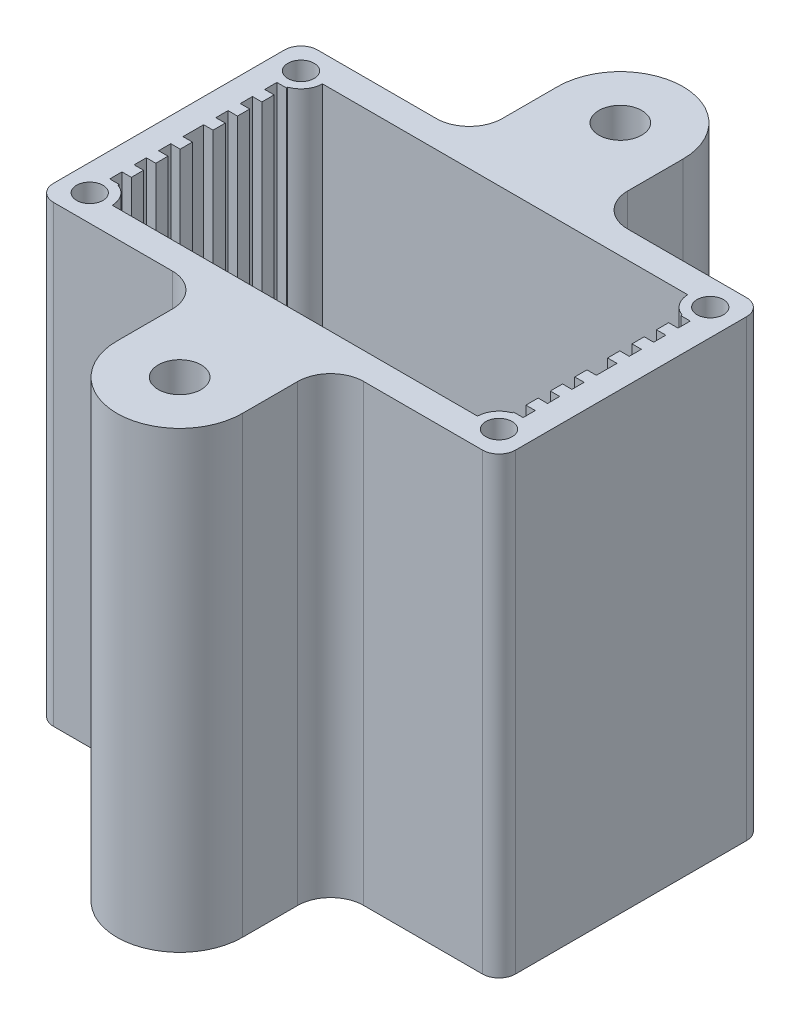
SolidWorks part; units mm, degrees
ref_plane "Front Plane" through (0, 0, 0) normal (0, 0, 1) x (1, 0, 0)
ref_plane "Top Plane" through (0, 0, 0) normal (0, 1, 0) x (1, 0, 0)
ref_plane "Right Plane" through (0, 0, 0) normal (1, 0, 0) x (0, 0, -1)
sketch "Sketch1" plane through (0, 0, 0) normal (0, 1, 0) x (1, 0, 0)
  line L0 (-48.5484, 0) -> (60.708, 0) construction
  line L1 (-31.8135, 16.1811) -> (31.8135, 16.1811) construction
  line L2 (-31.8135, 16.1811) -> (-31.8135, -16.1811) construction
  line L3 (-31.8135, -16.1811) -> (31.8135, -16.1811) construction
  line L4 (31.8135, 16.1811) -> (31.8135, -16.1811) construction
  line L5 (-31.8135, 16.1811) -> (31.8135, -16.1811) construction
  line L6 (-31.8135, -16.1811) -> (31.8135, 16.1811) construction
  line L11 (-30.3657, -16.1811) -> (30.3657, -16.1811) construction
  line L12 (-30.3657, -16.1811) -> (-30.3657, 16.1811) construction
  line L13 (-30.3657, 16.1811) -> (30.3657, 16.1811) construction
  line L14 (30.3657, -16.1811) -> (30.3657, 16.1811) construction
  line L15 (-30.3657, -16.1811) -> (30.3657, 16.1811) construction
  line L16 (-30.3657, 16.1811) -> (30.3657, -16.1811) construction
  line L17 (-31.8135, 10.9868) -> (31.8135, 10.9868) construction
  line L18 (-31.8135, 16.1811) -> (31.8135, 16.1811) construction
  line L19 (-31.8135, 16.1811) -> (-31.8135, 12.8664) construction
  line L20 (-31.8135, 12.8664) -> (31.8135, 12.8664) construction
  line L21 (31.8135, 16.1811) -> (31.8135, 12.8664) construction
  line L22 (-31.8135, 9.1072) -> (31.8135, 9.1072) construction
  line L23 (-31.8135, 7.2276) -> (31.8135, 7.2276) construction
  line L24 (-31.8135, 5.348) -> (31.8135, 5.348) construction
  line L25 (-31.8135, 3.4684) -> (31.8135, 3.4684) construction
  line L26 (-31.8135, 1.5888) -> (31.8135, 1.5888) construction
  line L27 (30.3657, 16.1811) -> (-30.3657, 16.1811)
  line L29 (-35.56, 0) -> (-35.56, 20.32)
  line L30 (-35.56, 20.32) -> (35.56, 20.32)
  line L31 (35.56, 0) -> (35.56, 20.32)
  line L32 (-33.4219, -19.0982) -> (35.56, 20.32) construction
  line L33 (-35.56, 20.32) -> (33.4219, -19.0982) construction
  line L34 (-30.3657, 16.1811) -> (-30.3657, 12.8664)
  line L35 (-30.3657, 12.8664) -> (-31.8135, 12.8664)
  line L36 (-31.8135, 12.8664) -> (-31.8135, 10.9868)
  line L37 (-31.8135, 10.9868) -> (-30.3657, 10.9868)
  line L38 (-30.3657, 10.9868) -> (-30.3657, 9.1072)
  line L39 (-30.3657, 9.1072) -> (-31.8135, 9.1072)
  line L40 (-31.8135, 9.1072) -> (-31.8135, 7.2276)
  line L41 (-31.8135, 7.2276) -> (-30.3657, 7.2276)
  line L42 (-30.3657, 7.2276) -> (-30.3657, 5.348)
  line L43 (-30.3657, 5.348) -> (-31.8135, 5.348)
  line L44 (-31.8135, 5.348) -> (-31.8135, 3.4684)
  line L45 (-31.8135, 3.4684) -> (-30.3657, 3.4684)
  line L46 (-30.3657, 3.4684) -> (-30.3657, 1.5888)
  line L47 (-30.3657, 1.5888) -> (-31.8135, 1.5888)
  line L48 (-31.8135, 1.5888) -> (-31.8135, 0)
  line L49 (-31.8135, 0) -> (-35.56, 0)
  line L50 (30.3657, 16.1811) -> (30.3657, 12.8664)
  line L51 (30.3657, 12.8664) -> (31.8135, 12.8664)
  line L52 (31.8135, 12.8664) -> (31.8135, 10.9868)
  line L53 (31.8135, 10.9868) -> (30.3657, 10.9868)
  line L54 (30.3657, 10.9868) -> (30.3657, 9.1072)
  line L55 (30.3657, 9.1072) -> (31.8135, 9.1072)
  line L56 (31.8135, 9.1072) -> (31.8135, 7.2276)
  line L57 (31.8135, 7.2276) -> (30.3657, 7.2276)
  line L58 (30.3657, 7.2276) -> (30.3657, 5.348)
  line L59 (30.3657, 5.348) -> (31.8135, 5.348)
  line L60 (31.8135, 5.348) -> (31.8135, 3.4684)
  line L61 (31.8135, 3.4684) -> (30.3657, 3.4684)
  line L62 (30.3657, 3.4684) -> (30.3657, 1.5888)
  line L63 (30.3657, 1.5888) -> (31.8135, 1.5888)
  line L64 (31.8135, 1.5888) -> (31.8135, 0)
  line L65 (31.8135, 0) -> (35.56, 0)
  point P0 (0, 0)
  point P6 (0, 0)
  point P27 (0, 0)
  dimension "D1" = 32.3621
  dimension "D2" = 63.627
  dimension "D3" = 60.7314
  dimension "D4" = 3.3147
  dimension "D5" = 1.8796
  dimension "D6" = 1.8796
  dimension "D7" = 1.8796
  dimension "D8" = 1.8796
  dimension "D9" = 1.8796
  dimension "D10" = 1.8796
  dimension "D12" = 20.32
  dimension "D11" = 35.56
  dimension "D13" = 35.56
extrude "Boss-Extrude1" add sketch "Sketch1" along normal blind 69.85
sketch "Sketch2" plane through (0, 0, 0) normal (0, 0, 1) x (1, 0, 0)
  line L0 (-31.8135, 69.85) -> (-35.56, 0) construction
  line L1 (-31.8135, 0) -> (-35.56, 69.85) construction
  line L2 (-35.56, 69.85) -> (-31.8135, 69.85) construction
  line L3 (-32.7469, 0) -> (-34.6265, 0)
  line L4 (-32.7469, 0) -> (-32.7469, 69.85)
  line L5 (-32.7469, 69.85) -> (-34.6265, 69.85)
  line L6 (-34.6265, 0) -> (-34.6265, 69.85)
  line L7 (-32.7469, 0) -> (-34.6265, 69.85) construction
  line L8 (-32.7469, 69.85) -> (-34.6265, 0) construction
  point P8 (-33.6867, 34.925)
  dimension "D1" = 1.8796
sketch "Sketch3" plane through (0, 0, 0) normal (0, 0, 1) x (1, 0, 0)
  line L0 (35.56, 69.85) -> (31.8135, 0) construction
  line L1 (35.56, 0) -> (31.8135, 69.85) construction
  line L2 (31.8135, 69.85) -> (35.56, 69.85) construction
  line L3 (32.7342, 0) -> (34.6392, 0)
  line L4 (32.7342, 0) -> (32.7342, 69.85)
  line L5 (32.7342, 69.85) -> (34.6392, 69.85)
  line L6 (34.6392, 0) -> (34.6392, 69.85)
  line L7 (32.7342, 0) -> (34.6392, 69.85) construction
  line L8 (32.7342, 69.85) -> (34.6392, 0) construction
  point P8 (33.6867, 34.925)
  dimension "D1" = 1.905
fillet "Fillet1" radius 2.54 2 edges at (-35.56, 34.925, -20.32) (35.56, 34.925, -20.32)
sketch "Sketch4" plane through (0, 0, 0) normal (0, 1, 0) x (1, 0, 0)
  line L0 (-35.56, 0) -> (35.56, 0) construction
  line L1 (0, 0) -> (0, 20.32) construction
  line L2 (33.02, 20.32) -> (-33.02, 20.32) construction
  line L4 (-9.652, 33.909) -> (-9.652, 20.32)
  line L5 (-9.652, 20.32) -> (9.652, 20.32)
  line L6 (9.652, 33.909) -> (9.652, 20.32)
  line L7 (0, 24.257) -> (0, 33.909) construction
  circle A0 centre (0, 33.909) radius 3.302
  arc A1 (9.652, 33.909) -> (-9.652, 33.909) centre (0, 33.909) ccw
  dimension "D2" = 6.604
  dimension "D3" = 19.304
  dimension "D1" = 33.909
extrude "Boss-Extrude3" add sketch "Sketch4" along normal through all
fillet "Fillet2" radius 5.08 2 edges at (-9.652, 34.925, -20.32) (9.652, 34.925, -20.32)
sketch "Sketch5" plane through (0, 69.85, 0) normal (0, 1, 0) x (1, 0, 0)
  line L0 (-31.496, 20.32) -> (-31.496, 16.256) construction
  line L1 (-14.732, 20.32) -> (-33.02, 20.32) construction
  line L2 (-31.496, 16.256) -> (-35.56, 16.256) construction
  line L3 (-35.56, 17.78) -> (-35.56, 0) construction
  circle A0 centre (-31.496, 16.256) radius 3.3896
extrude "Boss-Extrude4" add sketch "Sketch5" against normal up to surface (69.85 mm away) up to face at (0, 0, -10.8816)
mirror "Mirror1" about plane through (0, 0, 0) normal (0, 0, 1) of "Boss-Extrude1", "Fillet1", "Boss-Extrude3", "Fillet2"
mirror "Mirror2" about plane through (0, 0, 0) normal (0, 0, 1) of "Boss-Extrude4" second plane through (0, 0, 0) second plane normal (1, 0, 0)
sketch "Sketch6" plane through (0, 69.85, 0) normal (0, 1, 0) x (1, 0, 0)
  line L0 (-31.496, 20.32) -> (-31.496, 16.256) construction
  line L1 (-14.732, 20.32) -> (-33.02, 20.32) construction
  line L2 (-31.496, 16.256) -> (-35.56, 16.256) construction
  line L3 (-35.56, 17.78) -> (-35.56, -17.78) construction
  circle A0 centre (-31.496, 16.256) radius 2.032
extrude "Cut-Extrude1" cut sketch "Sketch6" against normal through all
mirror "Mirror3" about plane through (0, 0, 0) normal (0, 0, 1) of "Cut-Extrude1" second plane through (0, 0, 0) second plane normal (1, 0, 0)
equation "\"D4@Sketch1\"=0.261/2"
equation "\"D13@Sketch1\"=\"D11@Sketch1\""
